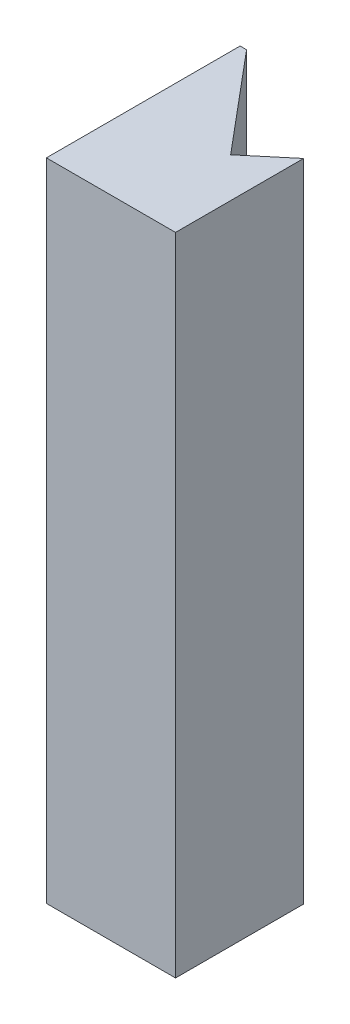
SolidWorks part; units mm, degrees
ref_plane "Front Plane" through (0, 0, 0) normal (0, 0, 1) x (1, 0, 0)
ref_plane "Top Plane" through (0, 0, 0) normal (0, 1, 0) x (1, 0, 0)
ref_plane "Right Plane" through (0, 0, 0) normal (1, 0, 0) x (0, 0, -1)
sketch "Sketch1" plane through (0, 0, 0) normal (0, 1, 0) x (1, 0, 0)
  line L0 (-26.0593, 36.2132) -> (-9.7325, 16.7557)
  line L1 (-1.9293, -1.8868) -> (-27.3293, -1.8868)
  line L2 (-1.9293, -1.8868) -> (-1.9293, 23.3034)
  line L3 (-27.3293, 36.2132) -> (-26.0593, 36.2132)
  line L4 (-27.3293, -1.8868) -> (-27.3293, 36.2132)
  line L7 (-9.7325, 16.7557) -> (-1.9293, 23.3034)
  point P0 (0, 0)
  dimension "D1" = 1.27
  dimension "D2" = 90
  dimension "D3" = 130
extrude "Boss-Extrude1" add sketch "Sketch1" along normal blind 127
